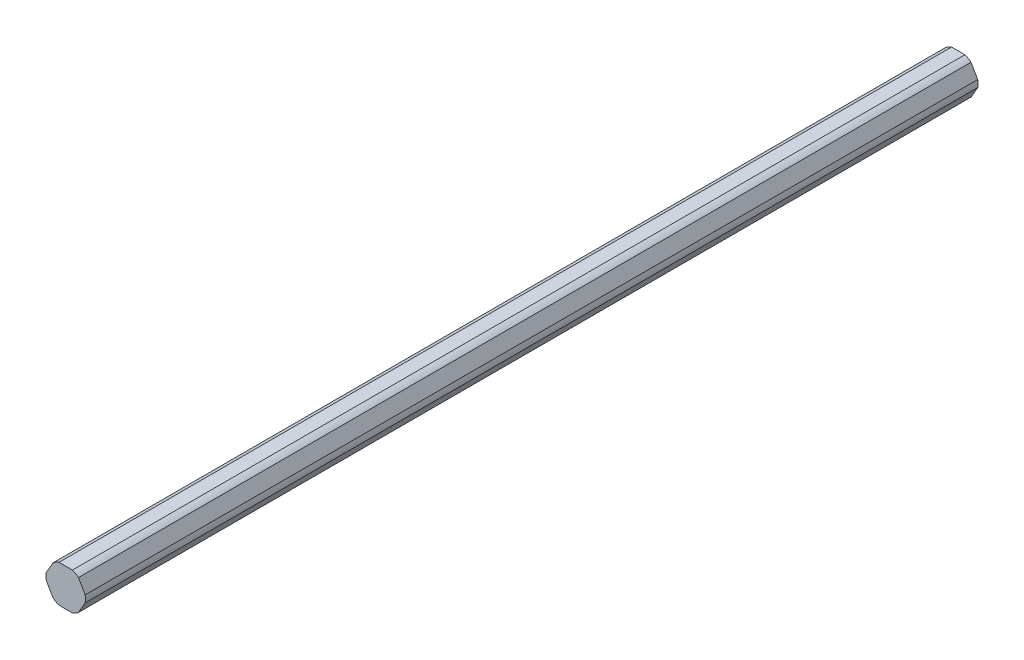
SolidWorks part; units mm, degrees
ref_plane "Front Plane" through (0, 0, 0) normal (0, 0, 1) x (1, 0, 0)
ref_plane "Top Plane" through (0, 0, 0) normal (0, 1, 0) x (1, 0, 0)
ref_plane "Right Plane" through (0, 0, 0) normal (1, 0, 0) x (0, 0, -1)
sketch "Sketch1" plane through (0, 0, 0) normal (0, 0, 1) x (1, 0, 0)
  line L1 (-7.3323, 0) -> (-3.6662, -6.35)
  line L2 (-3.6662, -6.35) -> (3.6662, -6.35)
  line L3 (3.6662, -6.35) -> (7.3323, 0)
  line L4 (7.3323, 0) -> (3.6662, 6.35)
  line L5 (3.6662, 6.35) -> (-3.6662, 6.35)
  line L6 (-3.6662, 6.35) -> (-7.3323, 0)
  circle A1 centre (0, 0) radius 6.35 construction
  circle A2 centre (0, 0) radius 6.75
  dimension "D2" = 13.5
  dimension "D1" = 12.7
extrude "Boss-Extrude1" add sketch "Sketch1" along normal blind 304.8 contours L4 A2 L5 L6 L1 L2 L3
ref_plane "Plane1" through (0, 0, 152.4) normal (0, 0, 1) x (1, 0, 0)
